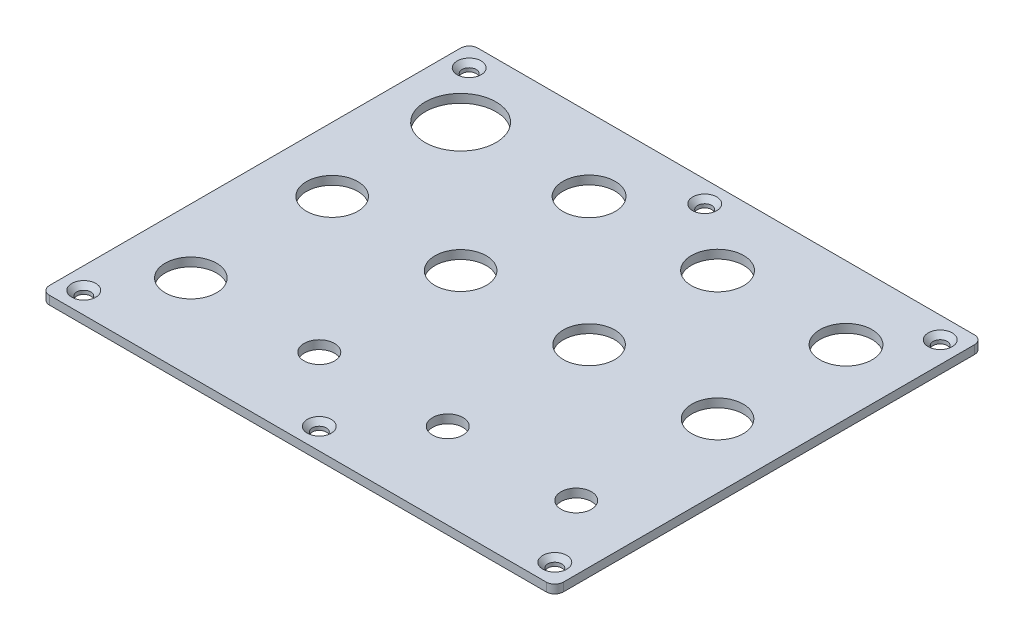
SolidWorks part; units mm, degrees
ref_plane "Front Plane" through (0, 0, 0) normal (0, 0, 1) x (1, 0, 0)
ref_plane "Top Plane" through (0, 0, 0) normal (0, 1, 0) x (1, 0, 0)
ref_plane "Right Plane" through (0, 0, 0) normal (1, 0, 0) x (0, 0, -1)
sketch "Bottom Plate" plane through (0, 0, 0) normal (0, 1, 0) x (1, 0, 0)
  line L1 (0, 0) -> (-120, 0)
  line L2 (0, 0) -> (0, 100)
  line L3 (0, 100) -> (-120, 100)
  line L4 (-120, 0) -> (-120, 100)
  dimension "D1" = 120
  dimension "D2" = 100
extrude "Bottom Plate EXT" add sketch "Bottom Plate" along normal blind 2
sketch "Middle Row" plane through (0, 2, 0) normal (0, 1, 0) x (1, 0, 0)
  line L0 (-120, 100) -> (-120, 0) construction
  line L1 (-120, 50) -> (0, 50) construction
  line L2 (0, 0) -> (0, 100) construction
  circle A0 centre (-105, 53) radius 6
  circle A1 centre (-75, 53) radius 6
  circle A2 centre (-45, 53) radius 6
  circle A3 centre (-15, 53) radius 6
  dimension "D1" = 12
  dimension "D2" = 30
  dimension "D6" = 30
  dimension "D3" = 30
  dimension "D4" = 15
  dimension "D5" = 3
extrude "Middle Row Cut" cut sketch "Middle Row" against normal through all
sketch "Top Row" plane through (0, 2, 0) normal (0, 1, 0) x (1, 0, 0)
  line L1 (-120, 100) -> (-120, 0) construction
  circle A0 centre (-105, 83) radius 8.25
  circle A1 centre (-75, 83) radius 6.1
  circle A2 centre (-45, 83) radius 6.1
  circle A3 centre (-15, 83) radius 6.1
  circle A6 centre (-105, 53) radius 6 construction
  dimension "D1" = 16.5
  dimension "D2" = 30
  dimension "D7" = 12.2
  dimension "D3" = 15
  dimension "D4" = 30
  dimension "D5" = 30
  dimension "D6" = 30
extrude "Top Row Cut" cut sketch "Top Row" against normal through all
sketch "Bottom Row" plane through (0, 2, 0) normal (0, 1, 0) x (1, 0, 0)
  line L1 (-120, 100) -> (-120, 0) construction
  circle A0 centre (-75, 20) radius 3.55
  circle A1 centre (-45, 20) radius 3.55
  circle A2 centre (-15, 20) radius 3.55
  circle A5 centre (-105, 20) radius 6
  circle A6 centre (-105, 53) radius 6 construction
  dimension "D1" = 7.1
  dimension "D2" = 33
  dimension "D3" = 30
  dimension "D4" = 30
  dimension "D5" = 30
  dimension "D6" = 15
extrude "Bottom Row Cut" cut sketch "Bottom Row" against normal through all
sketch "Plate Screws" plane through (0, 2, 0) normal (0, 1, 0) x (1, 0, 0)
  line L0 (0, 100) -> (-120, 100) construction
  line L1 (-120, 100) -> (-120, 0) construction
  line L2 (-120, 0) -> (0, 0) construction
  line L3 (0, 0) -> (0, 100) construction
  line L4 (-60, 100) -> (-60, 59.8221) construction
  line L5 (0, 50) -> (-30.2044, 50) construction
  circle A0 centre (-115, 95) radius 1.65
  circle A1 centre (-5, 95) radius 1.65
  circle A2 centre (-5, 5) radius 1.65
  circle A3 centre (-115, 5) radius 1.65
  circle A4 centre (-60, 95) radius 1.65
  circle A5 centre (-60, 5) radius 1.65
  dimension "D1" = 3.3
  dimension "D2" = 5
  dimension "D3" = 5
  dimension "D4" = 5
  dimension "D5" = 5
extrude "Plate Screws Cut" cut sketch "Plate Screws" against normal through all
sketch "Plate Screw Head" plane through (0, 2, 0) normal (0, 1, 0) x (1, 0, 0)
  line L0 (-60, 100) -> (-60, 73.7034) construction
  line L1 (0, 100) -> (-120, 100) construction
  line L2 (0, 50) -> (-52.6177, 50) construction
  line L3 (0, 0) -> (0, 100) construction
  circle A0 centre (-115, 95) radius 2.8
  circle A1 centre (-5, 95) radius 2.8
  circle A2 centre (-5, 5) radius 2.8
  circle A3 centre (-115, 5) radius 2.8
  circle A4 centre (-60, 95) radius 2.8
  circle A5 centre (-60, 5) radius 2.8
  dimension "D1" = 5.6
extrude "Plate Screw Head Cut" cut sketch "Plate Screw Head" against normal blind 2 draft 45
fillet "Fillet1" radius 2 1 edges at (-120, 1, -100)
fillet "Fillet2" radius 2 1 edges at (0, 1, -100)
fillet "Fillet3" radius 2 1 edges at (0, 1, 0)
fillet "Fillet4" radius 2 1 edges at (-120, 1, 0)
